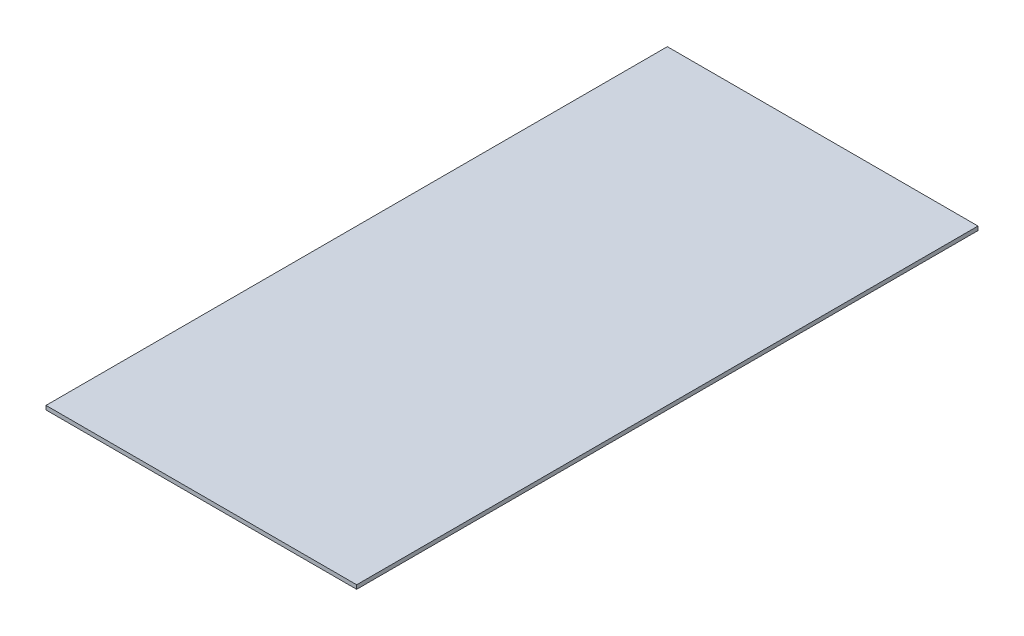
SolidWorks part; units mm, degrees
material "5052-H32"
ref_plane "Front Plane" through (0, 0, 0) normal (0, 0, 1) x (1, 0, 0)
ref_plane "Top Plane" through (0, 0, 0) normal (0, 1, 0) x (1, 0, 0)
ref_plane "Right Plane" through (0, 0, 0) normal (1, 0, 0) x (0, 0, -1)
sketch "Sketch1" plane through (0, 0, 0) normal (0, 1, 0) x (1, 0, 0)
  line L1 (-123.825, 247.65) -> (123.825, 247.65)
  line L2 (-123.825, 247.65) -> (-123.825, -247.65)
  line L3 (-123.825, -247.65) -> (123.825, -247.65)
  line L4 (123.825, 247.65) -> (123.825, -247.65)
  line L5 (-123.825, 247.65) -> (123.825, -247.65) construction
  line L6 (-123.825, -247.65) -> (123.825, 247.65) construction
  point P0 (0, 0)
  dimension "D1" = 495.3
  dimension "D2" = 247.65
extrude "Boss-Extrude1" add sketch "Sketch1" along normal mid plane 3.175
